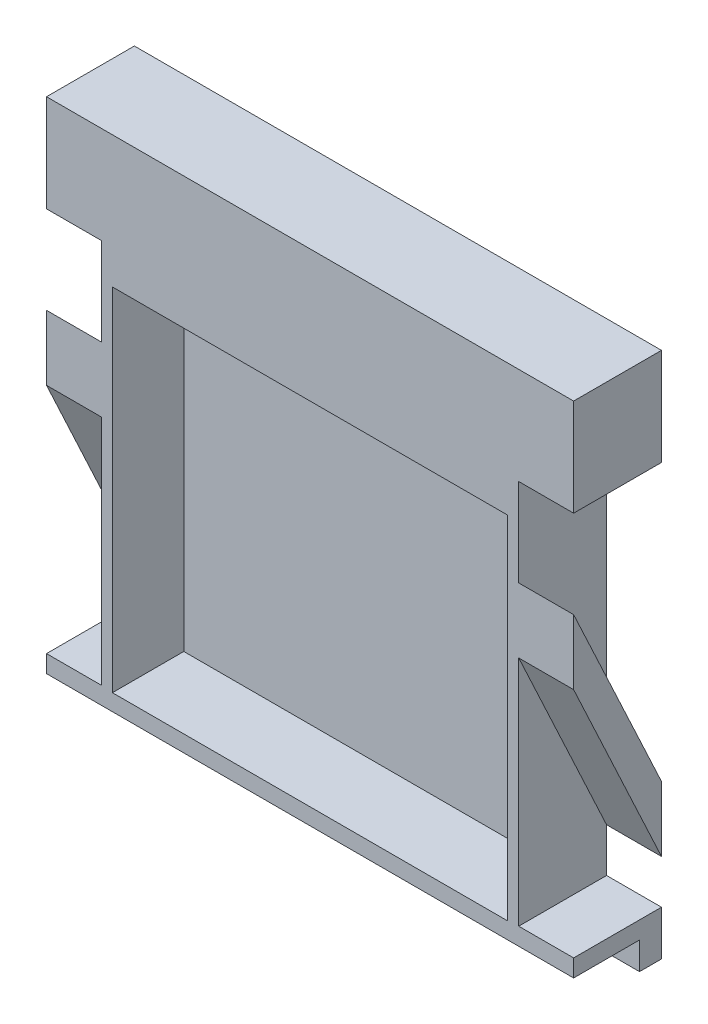
SolidWorks part; units mm, degrees
ref_plane "Front Plane" through (0, 0, 0) normal (0, 0, 1) x (1, 0, 0)
ref_plane "Top Plane" through (0, 0, 0) normal (0, 1, 0) x (1, 0, 0)
ref_plane "Right Plane" through (0, 0, 0) normal (1, 0, 0) x (0, 0, -1)
sketch "Sketch1" plane through (0, 0, 0) normal (0, 0, 1) x (1, 0, 0)
  line L0 (-152.4, -152.4) -> (152.4, -152.4)
  line L1 (-152.4, -152.4) -> (-152.4, 152.4)
  line L2 (152.4, -152.4) -> (152.4, 152.4)
  line L3 (-152.4, 152.4) -> (152.4, 152.4)
  line L4 (-152.4, -152.4) -> (152.4, 152.4) construction
  line L5 (152.4, -152.4) -> (-152.4, 152.4) construction
  line L6 (-152.4, 0) -> (152.4, 0) construction
  point P1 (0, 0)
  dimension "D1" = 304.8
  dimension "D2" = 304.8
extrude "Blank" add sketch "Sketch1" along normal blind 50.8
sketch "Sketch2" plane through (0, 0, 50.8) normal (0, 0, 1) x (1, 0, 0)
  line L0 (114.3, -127) -> (-114.3, -127)
  line L1 (114.3, -127) -> (114.3, 76.2)
  line L2 (-114.3, -127) -> (-114.3, 76.2)
  line L3 (114.3, 76.2) -> (-114.3, 76.2)
  line L4 (114.3, -127) -> (-114.3, 76.2) construction
  line L5 (-114.3, -127) -> (114.3, 76.2) construction
  line L6 (0, -152.4) -> (0, 152.4) construction
  line L7 (-152.4, -152.4) -> (152.4, -152.4) construction
  line L8 (152.4, 152.4) -> (-152.4, 152.4) construction
  point P1 (0, -25.4)
  dimension "D1" = 228.6
  dimension "D2" = 203.2
  dimension "D3" = 25.4
extrude "Rough battery cavity" cut sketch "Sketch2" against normal blind 41.275
sketch "Sketch3" plane through (0, 0, 50.8) normal (0, 0, 1) x (1, 0, 0)
  line L0 (-152.4, -152.4) -> (152.4, -152.4)
  line L1 (-152.4, -152.4) -> (-152.4, -136.525)
  line L2 (152.4, -152.4) -> (152.4, -136.525)
  line L3 (-152.4, -136.525) -> (152.4, -136.525)
  dimension "D1" = 15.875
extrude "Bumper rail" cut sketch "Sketch3" against normal blind 38.1
sketch "Sketch4" plane through (0, 0, 12.7) normal (0, 0, 1) x (1, 0, 0)
  line L0 (152.4, -136.525) -> (-152.4, -136.525) construction
  line L1 (0, -146.05) -> (0, 0) construction
  line L3 (-127, -146.05) -> (-63.5, -146.05) construction
  line L4 (-63.5, -146.05) -> (0, -146.05) construction
  line L5 (0, -146.05) -> (63.5, -146.05) construction
  line L6 (63.5, -146.05) -> (127, -146.05) construction
  line L7 (-152.4, -152.4) -> (152.4, -152.4) construction
  circle A0 centre (-127, -146.05) radius 3.302
  circle A1 centre (127, -146.05) radius 3.302
  circle A2 centre (-63.5, -146.05) radius 3.302
  circle A3 centre (0, -146.05) radius 3.302
  circle A4 centre (63.5, -146.05) radius 3.302
  dimension "D1" = 254
  dimension "D3" = 6.604
  dimension "D2" = 6.35
extrude "Bumper rail holes" cut sketch "Sketch4" against normal through all
sketch "Sketch5" plane through (152.4, 0, 0) normal (1, 0, 0) x (0, 0, -1)
  line L0 (-50.8, 45.441) -> (0, -63.5)
  line L1 (-50.8, -136.525) -> (-50.8, 152.4) construction
  line L2 (0, -152.4) -> (0, 152.4) construction
  line L3 (0, -63.5) -> (0, 96.241)
  line L4 (0, 96.241) -> (-50.8, 96.241)
  line L5 (-50.8, 96.241) -> (-50.8, 45.441)
  line L6 (0, -63.5) -> (-50.8, -63.5) construction
  line L7 (-50.8, -25.4) -> (0, -25.4) construction
  line L8 (-50.8, -127) -> (-50.8, 76.2) construction
  line L9 (-50.8, 7.8775) -> (0, -101.0635)
  line L10 (0, -101.0635) -> (0, -126.4635)
  line L11 (0, -126.4635) -> (-50.8, -126.4635)
  line L12 (-50.8, -126.4635) -> (-50.8, 7.8775)
  dimension "D1" = 65
  dimension "D2" = 15.875
  dimension "D3" = 38.1
  dimension "D4" = 25.4
extrude "Drive motor rail" cut sketch "Sketch5" against normal blind 31.75
mirror "Drive motor rail mirror" about plane through (0, 0, 0) normal (1, 0, 0) of "Drive motor rail"
